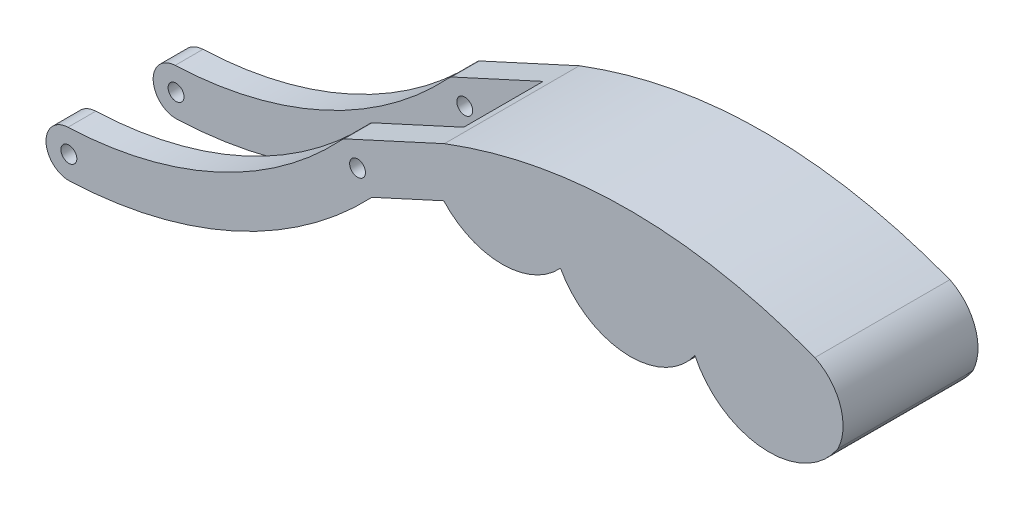
SolidWorks part; units mm, degrees
ref_plane "Alzado" through (0, 0, 0) normal (0, 0, 1) x (1, 0, 0)
ref_plane "Planta" through (0, 0, 0) normal (0, 1, 0) x (1, 0, 0)
ref_plane "Vista lateral" through (0, 0, 0) normal (1, 0, 0) x (0, 0, -1)
sketch "Croquis1" plane through (0, 0, 0) normal (0, 0, 1) x (1, 0, 0)
  line L0 (0, 0) -> (109.0871, 50) construction
  line L1 (0, 0) -> (109.0871, 0) construction
  line L2 (0, 0) -> (0, 50) construction
  line L3 (0, 50) -> (109.0871, 50) construction
  line L4 (109.0871, 0) -> (109.0871, 50) construction
  line L5 (-3.5418, 7.7272) -> (105.5454, 57.7272)
  line L6 (3.5418, -7.7272) -> (112.6289, 42.2728)
  line L7 (105.5454, 57.7272) -> (141.9077, 74.3939)
  line L8 (141.9077, 74.3939) -> (281.9077, 74.3939) construction
  line L9 (137.5866, 44.3939) -> (295.5187, 44.3939) construction
  line L10 (112.6289, 42.2728) -> (141.6607, 55.5795)
  line L11 (-91.42, 190.7902) -> (496.581, 7.0587) construction
  line L12 (-106.6165, 169.148) -> (-76.2235, 212.4324) construction
  circle A0 centre (0, 0) radius 3
  circle A1 centre (109.0871, 50) radius 3
  arc A2 (-3.5418, 7.7272) -> (3.5418, -7.7272) centre (0, 0) ccw
  arc A3 (112.6289, 42.2728) -> (105.5454, 57.7272) centre (109.0871, 50) ccw
  arc A4 (141.6607, 55.5795) -> (185.7693, 55.5795) centre (163.715, 75.6745) ccw
  arc A5 (185.7693, 55.5795) -> (236.5692, 52.4119) centre (212.1557, 69.8157) ccw
  arc A6 (236.5692, 52.4119) -> (290.5982, 48.9261) centre (264.5615, 65.8243) ccw
  arc A7 (0, 0) -> (109.0871, 50) centre (-6.2913, 157.726) ccw construction
  arc A8 (290.5982, 48.9261) -> (281.9077, 74.3939) centre (273.5191, 57.3148) ccw
  arc A9 (0.3447, -8.6416) -> (115.4086, 44.0978) centre (-6.2913, 157.726) ccw
  arc A10 (-0.3447, 8.6416) -> (102.7657, 55.9022) centre (-6.2913, 157.726) ccw
  arc A11 (-0.3447, 8.6416) -> (0.3447, -8.6416) centre (0, 0) ccw
  arc A12 (115.4086, 44.0978) -> (102.7657, 55.9022) centre (109.0871, 50) ccw
  spline S0 degree 2 poles (141.9077, 74.3939) (211.7052, 100.8392) (281.9077, 74.3939) knots 0 0 0 1 1 1
  point P7 (54.5436, 25)
  point P20 (185.7693, 55.5795)
  point P21 (236.5692, 52.4119)
  point P29 (59.4801, 14.2297)
  dimension "D3" = 6
  dimension "D4" = 6
  dimension "D1" = 120
  dimension "D2" = 50
  dimension "D5" = 40
  dimension "D6" = 140
  dimension "D7" = 30
extrude "Saliente-Extruir1" add sketch "Croquis1" along normal blind 51 contours S0 L7 A12 A9 L10 A4 A5 A6 A8 | A9 A12 L7 A3 L10 | L5 A12 A10 A11 A2 L6 A3 A0 A1 | L5 A11 A9 L10 L6 A2
sketch "Croquis2" plane through (-3.5418, 7.7272, 0) normal (-0.4167, 0.9091, 0) x (0.9091, 0.4167, 0)
  line L1 (-173.5002, -10.5) -> (156.4998, -10.5)
  line L2 (-173.5002, -10.5) -> (-173.5002, -40.5)
  line L3 (-173.5002, -40.5) -> (156.4998, -40.5)
  line L4 (156.4998, -10.5) -> (156.4998, -40.5)
  line L5 (-173.5002, -10.5) -> (156.4998, -40.5) construction
  line L6 (-173.5002, -40.5) -> (156.4998, -10.5) construction
  point P0 (-8.5002, -25.5)
  dimension "D1" = 30
  dimension "D2" = 330
extrude "Cortar-Extruir1" cut sketch "Croquis2" against normal through all both and the other way through all
